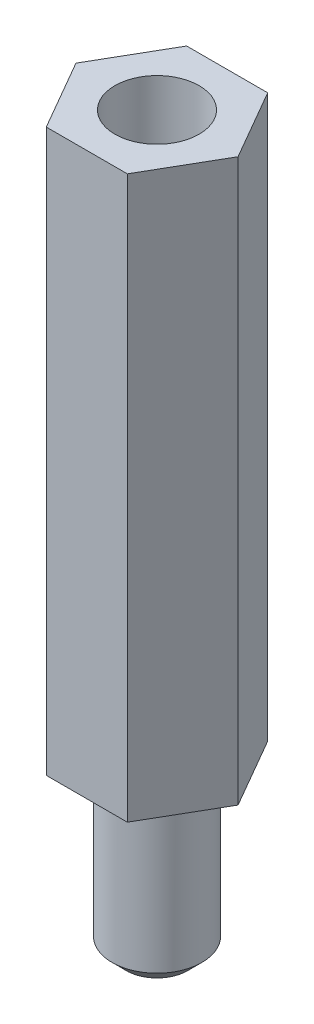
SolidWorks part; units mm, degrees
material "Alloy Steel"
ref_plane "Front Plane" through (0, 0, 0) normal (0, 0, 1) x (1, 0, 0)
ref_plane "Top Plane" through (0, 0, 0) normal (0, 1, 0) x (1, 0, 0)
ref_plane "Right Plane" through (0, 0, 0) normal (1, 0, 0) x (0, 0, -1)
sketch "Sketch1" plane through (0, 0, 0) normal (0, 1, 0) x (1, 0, 0)
  line L0 (0, 0) -> (0, 2.5) construction
  line L1 (-1.4434, 2.5) -> (1.4434, 2.5)
  line L2 (1.4434, 2.5) -> (2.8868, 0)
  line L3 (2.8868, 0) -> (1.4434, -2.5)
  line L4 (1.4434, -2.5) -> (-1.4434, -2.5)
  line L5 (-1.4434, -2.5) -> (-2.8868, 0)
  line L6 (-2.8868, 0) -> (-1.4434, 2.5)
  circle A0 centre (0, 0) radius 1.5
  dimension "D2" = 3
  dimension "D1" = 5
  dimension "D3" = 2.5
extrude "Extrude1" add sketch "Sketch1" along normal blind 20
sketch "Sketch2" plane through (0, 0, 0) normal (0, -1, 0) x (1, 0, 0)
  circle A0 centre (0, 0) radius 1.6
  dimension "D1" = 3.2
extrude "Extrude2" add sketch "Sketch2" along normal blind 6 and the other way blind 12
chamfer "Chamfer1" distance 0.5 angle 45 1 edges at (0, -6, -1.6)
fillet "Fillet1" radius 0.5 1 edges at (0, 0, 1.6)
fillet "Fillet2" radius 1 1 edges at (0, 12, -1.5)
